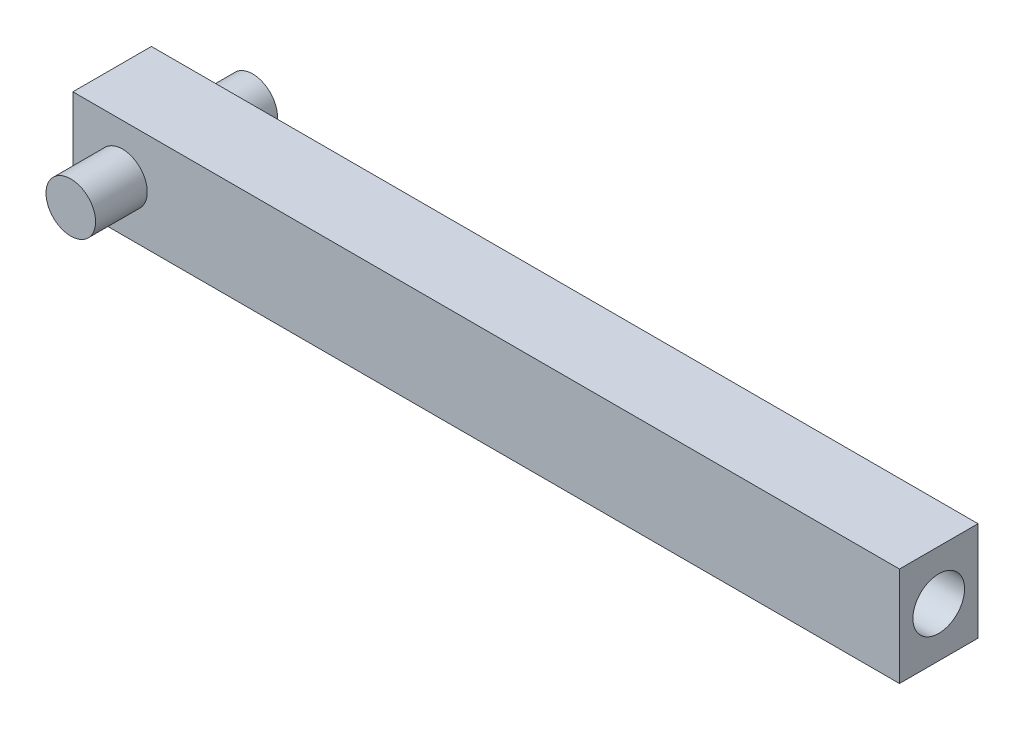
SolidWorks part; units mm, degrees
ref_plane "Front Plane" through (0, 0, 0) normal (0, 0, 1) x (1, 0, 0)
ref_plane "Top Plane" through (0, 0, 0) normal (0, 1, 0) x (1, 0, 0)
ref_plane "Right Plane" through (0, 0, 0) normal (1, 0, 0) x (0, 0, -1)
sketch "Sketch1" plane through (0, 0, 0) normal (0, 1, 0) x (1, 0, 0)
  line L1 (-200, 19) -> (200, 19)
  line L2 (-200, 19) -> (-200, -19)
  line L3 (-200, -19) -> (200, -19)
  line L4 (200, 19) -> (200, -19)
  line L5 (-200, 19) -> (200, -19) construction
  line L6 (-200, -19) -> (200, 19) construction
  point P0 (0, 0)
  dimension "D1" = 38
  dimension "D2" = 400
extrude "Boss-Extrude1" add sketch "Sketch1" along normal blind 48
sketch "Sketch2" plane through (0, 0, 19) normal (0, 0, 1) x (1, 0, 0)
  line L0 (-200, 48) -> (200, 48) construction
  line L1 (-200, 48) -> (-200, 0) construction
  circle A0 centre (-176, 24) radius 12
  dimension "D1" = 24
  dimension "D2" = 24
  dimension "D3" = 24
extrude "Boss-Extrude2" add sketch "Sketch2" along normal blind 25
sketch "Sketch3" plane through (0, 0, -19) normal (0, 0, -1) x (-1, 0, 0)
  line L0 (200, 48) -> (200, 0) construction
  line L1 (-200, 48) -> (200, 48) construction
  circle A0 centre (176, 24) radius 12
  dimension "D1" = 24
  dimension "D2" = 24
  dimension "D3" = 24
extrude "Boss-Extrude3" add sketch "Sketch3" along normal blind 25
sketch "Sketch6" plane through (200, 0, 0) normal (1, 0, 0) x (0, 0, -1)
  line L0 (-19, 48) -> (19, 48) construction
  line L1 (-19, 36) -> (-19, 12) construction
  circle A0 centre (0, 24) radius 12.5
  dimension "D1" = 25
  dimension "D2" = 24
  dimension "D3" = 19
extrude "Cut-Extrude1" cut sketch "Sketch6" against normal blind 50
